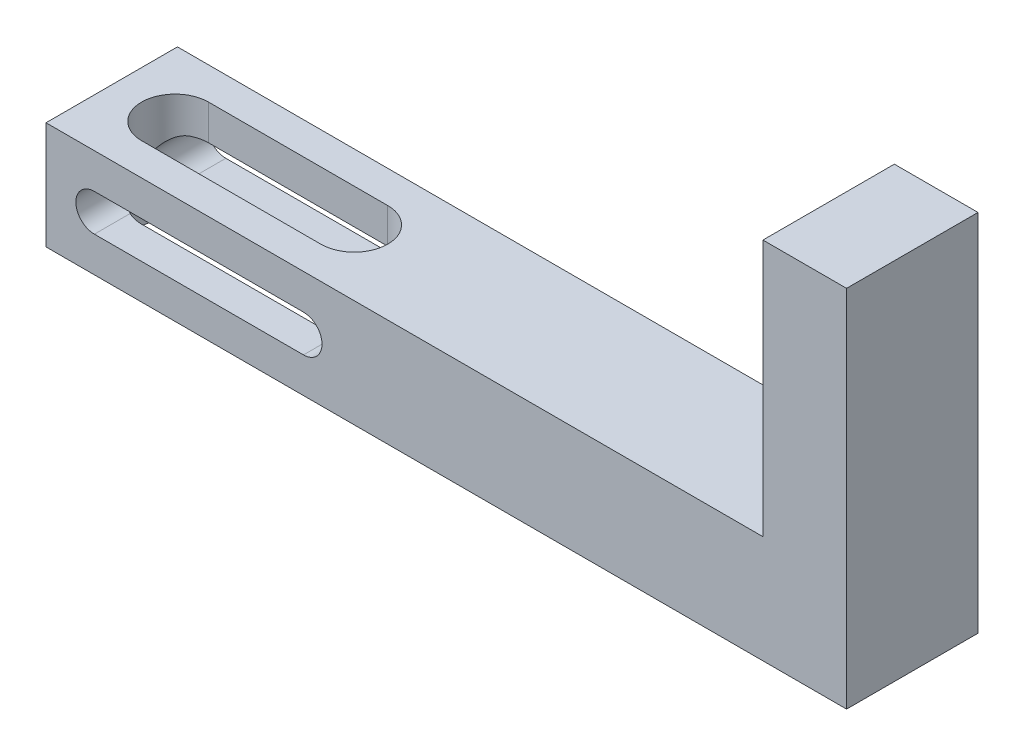
SolidWorks part; units mm, degrees
ref_plane "Front Plane" through (0, 0, 0) normal (0, 0, 1) x (1, 0, 0)
ref_plane "Top Plane" through (0, 0, 0) normal (0, 1, 0) x (1, 0, 0)
ref_plane "Right Plane" through (0, 0, 0) normal (1, 0, 0) x (0, 0, -1)
sketch "Sketch1" plane through (0, 0, 0) normal (0, 0, 1) x (1, 0, 0)
  line L0 (0, 0) -> (67, 0)
  line L1 (67, 0) -> (67, 30.5)
  line L2 (67, 30.5) -> (60, 30.5)
  line L3 (60, 30.5) -> (60, 9)
  line L4 (60, 9) -> (0, 9)
  line L5 (0, 9) -> (0, 0)
  dimension "D1" = 9
  dimension "D2" = 7
  dimension "D3" = 21.5
  dimension "D4" = 60
extrude "Boss-Extrude1" add sketch "Sketch1" against normal blind 11
sketch "Sketch2" plane through (0, 0, 0) normal (0, -1, 0) x (1, 0, 0)
  line L0 (0, -5.5) -> (67, -5.5) construction
  line L1 (0, -11) -> (0, 0) construction
  line L2 (67, -11) -> (67, 0) construction
  line L3 (5.3, -5.5) -> (20.3, -5.5) construction
  line L4 (5.3, -2.7) -> (20.3, -2.7)
  line L5 (5.3, -8.3) -> (20.3, -8.3)
  arc A0 (5.3, -2.7) -> (5.3, -8.3) centre (5.3, -5.5) ccw
  arc A1 (20.3, -8.3) -> (20.3, -2.7) centre (20.3, -5.5) ccw
  point P8 (12.8, -5.5)
  point P13 (2.5, -5.5)
  dimension "D1" = 5.6
  dimension "D2" = 2.5
  dimension "D3" = 15
extrude "Cut-Extrude1" cut sketch "Sketch2" against normal through all contours L5 A1 L4 A0
sketch "Sketch3" plane through (0, 0, 0) normal (0, 0, 1) x (1, 0, 0)
  line L0 (0, 4.5) -> (67, 4.5) construction
  line L1 (0, 9) -> (0, 0) construction
  line L2 (67, 0) -> (67, 30.5) construction
  line L3 (4.05, 4.5) -> (21.55, 4.5) construction
  line L4 (4.05, 6.05) -> (21.55, 6.05)
  line L5 (4.05, 2.95) -> (21.55, 2.95)
  line L6 (0, 0) -> (67, 0) construction
  arc A0 (4.05, 6.05) -> (4.05, 2.95) centre (4.05, 4.5) ccw
  arc A1 (21.55, 2.95) -> (21.55, 6.05) centre (21.55, 4.5) ccw
  point P8 (12.8, 4.5)
  point P13 (2.5, 4.5)
  dimension "D1" = 3.1
  dimension "D2" = 2.5
  dimension "D3" = 17.5
extrude "Cut-Extrude2" cut sketch "Sketch3" against normal through all
